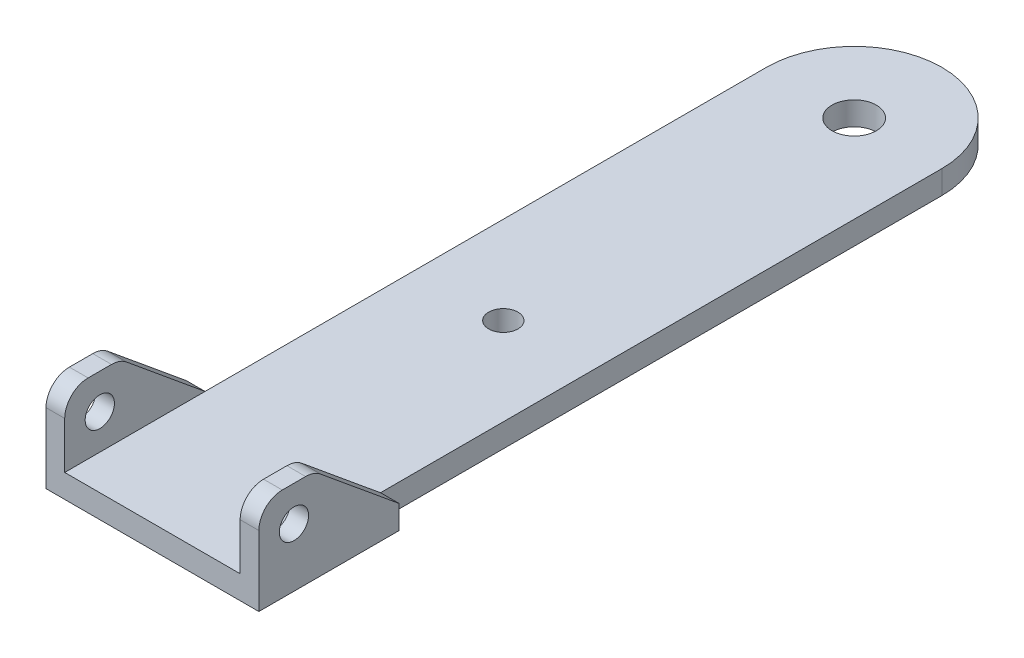
SolidWorks part; units mm, degrees
material "Plain Carbon Steel"
ref_plane "Front Plane" through (0, 0, 0) normal (0, 0, 1) x (1, 0, 0)
ref_plane "Top Plane" through (0, 0, 0) normal (0, 1, 0) x (1, 0, 0)
ref_plane "Right Plane" through (0, 0, 0) normal (1, 0, 0) x (0, 0, -1)
sketch "Sketch1" plane through (0, 0, 0) normal (0, 1, 0) x (1, 0, 0)
  line L0 (0, 0) -> (0, -150) construction
  line L1 (-37.5, 0) -> (37.5, 0) construction
  line L2 (-37.5, 0) -> (-37.5, -300)
  line L3 (-37.5, -300) -> (37.5, -300)
  line L4 (37.5, 0) -> (37.5, -300)
  arc A0 (-37.5, 0) -> (37.5, 0) centre (0, 0) cw
  circle A1 centre (0, -150) radius 6.25
  circle A2 centre (0, 0) radius 9.5
  dimension "D2" = 12.5
  dimension "D3" = 19
  dimension "D1" = 75
  dimension "D4" = 150
  dimension "D5" = 150
extrude "Boss-Extrude1" add sketch "Sketch1" along normal blind 10
sketch "Sketch2" plane through (0, 0, 0) normal (1, 0, 0) x (0, 0, -1)
  line L0 (-300, 10) -> (-300, 0) construction
  circle A0 centre (-300, 5) radius 12.5
  dimension "D1" = 25
extrude "Boss-Extrude2" [suppressed] add sketch "Sketch2" along normal mid plane 75
sketch "Sketch3" [suppressed] plane through (37.5, 0, 0) normal (1, 0, 0) x (0, 0, -1)
  circle A0 centre (-300, 5) radius 6.25
  arc A1 (-288.5436, 10) -> (-288.5436, 0) centre (-300, 5) ccw construction
  dimension "D1" = 12.5
extrude "Cut-Extrude1" [suppressed] cut sketch "Sketch3" against normal through all
sketch "Sketch4" plane through (37.5, 0, 0) normal (1, 0, 0) x (0, 0, -1)
  line L0 (-240, 0) -> (-240, 10)
  line L1 (-300, 0) -> (0, 0) construction
  line L2 (-300, 10) -> (0, 10) construction
  line L3 (-240, 10) -> (-273.6411, 37.7178)
  line L4 (-280, 40) -> (-290, 40)
  line L5 (-300, 30) -> (-300, 0)
  line L6 (-300, 0) -> (-240, 0)
  line L7 (-300, 10) -> (-300, 0) construction
  line L8 (-300, 25) -> (-285, 25) construction
  line L9 (-285, 25) -> (-285, 40) construction
  line L10 (-285, 25) -> (-285, 10) construction
  circle A0 centre (-285, 25) radius 6.25
  arc A1 (-273.6411, 37.7178) -> (-280, 40) centre (-280, 30) ccw
  arc A2 (-300, 30) -> (-290, 40) centre (-290, 30) cw
  point P8 (-270.3295, 37.4181)
  point P16 (0, 0)
  point P22 (-300, 40)
  dimension "D1" = 12.5
  dimension "D3" = 10
  dimension "D4" = 10
  dimension "D2" = 40
  dimension "D5" = 60
extrude "Boss-Extrude3" add sketch "Sketch4" along normal blind 8
mirror "Mirror1" about plane through (0, 0, 0) normal (1, 0, 0) of "Boss-Extrude3"
